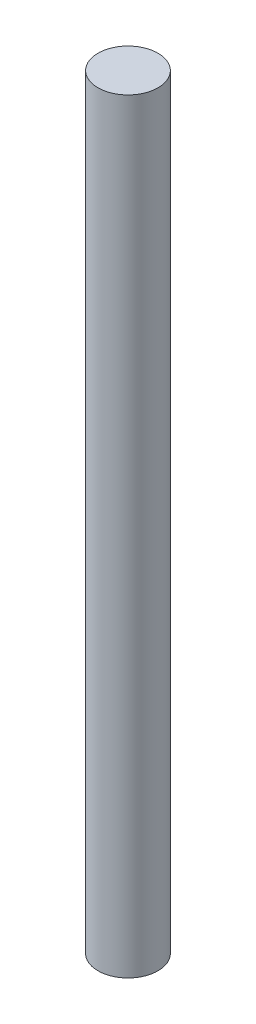
SolidWorks part; units mm, degrees
ref_plane "Front Plane" through (0, 0, 0) normal (0, 0, 1) x (1, 0, 0)
ref_plane "Top Plane" through (0, 0, 0) normal (0, 1, 0) x (1, 0, 0)
ref_plane "Right Plane" through (0, 0, 0) normal (1, 0, 0) x (0, 0, -1)
sketch "Sketch1" plane through (0, 0, 0) normal (0, 1, 0) x (1, 0, 0)
  circle A0 centre (0, 0) radius 4
  dimension "D1" = 8
extrude "Boss-Extrude1" add sketch "Sketch1" along normal blind 102
sketch "Sketch2" plane through (0, 102, 0) normal (0, 1, 0) x (1, 0, 0)
  circle A0 centre (0, 0) radius 3
  dimension "D1" = 6
